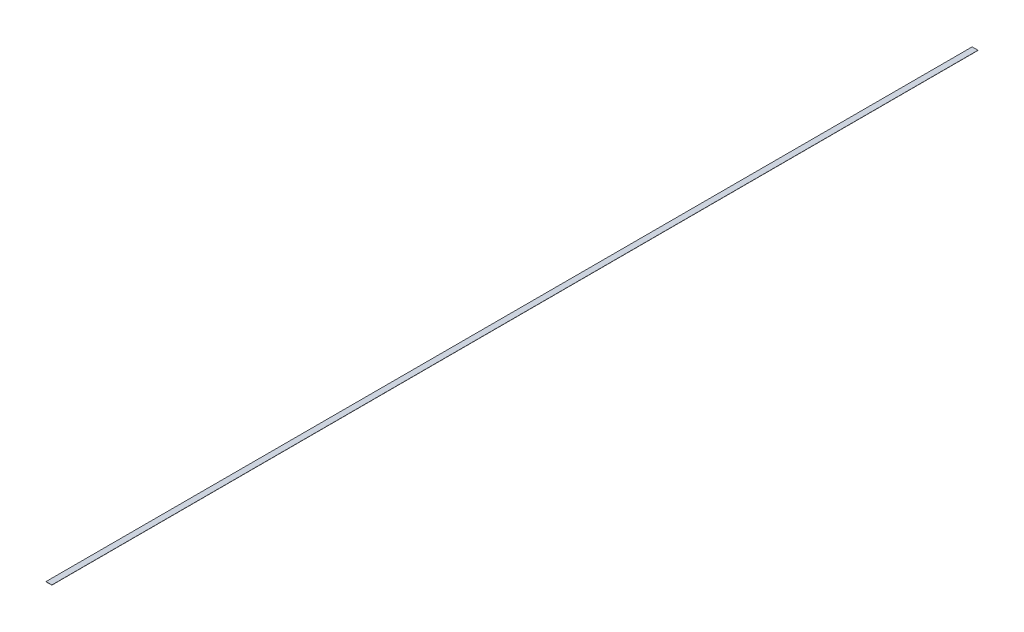
SolidWorks part; units mm, degrees
ref_plane "Front Plane" through (0, 0, 0) normal (0, 0, 1) x (1, 0, 0)
ref_plane "Top Plane" through (0, 0, 0) normal (0, 1, 0) x (1, 0, 0)
ref_plane "Right Plane" through (0, 0, 0) normal (1, 0, 0) x (0, 0, -1)
sketch "Sketch1" plane through (0, 0, 0) normal (0, 1, 0) x (1, 0, 0)
  line L1 (-25.4, 4008.755) -> (25.4, 4008.755)
  line L2 (-25.4, 4008.755) -> (-25.4, -4008.755)
  line L3 (-25.4, -4008.755) -> (25.4, -4008.755)
  line L4 (25.4, 4008.755) -> (25.4, -4008.755)
  line L5 (0, -4008.755) -> (0, 4008.755) construction
  line L6 (-25.4, 0) -> (25.4, 0) construction
  point P0 (0, 0)
  dimension "D1" = 8017.51
  dimension "D2" = 50.8
extrude "Boss-Extrude1" add sketch "Sketch1" along normal blind 1.5875
